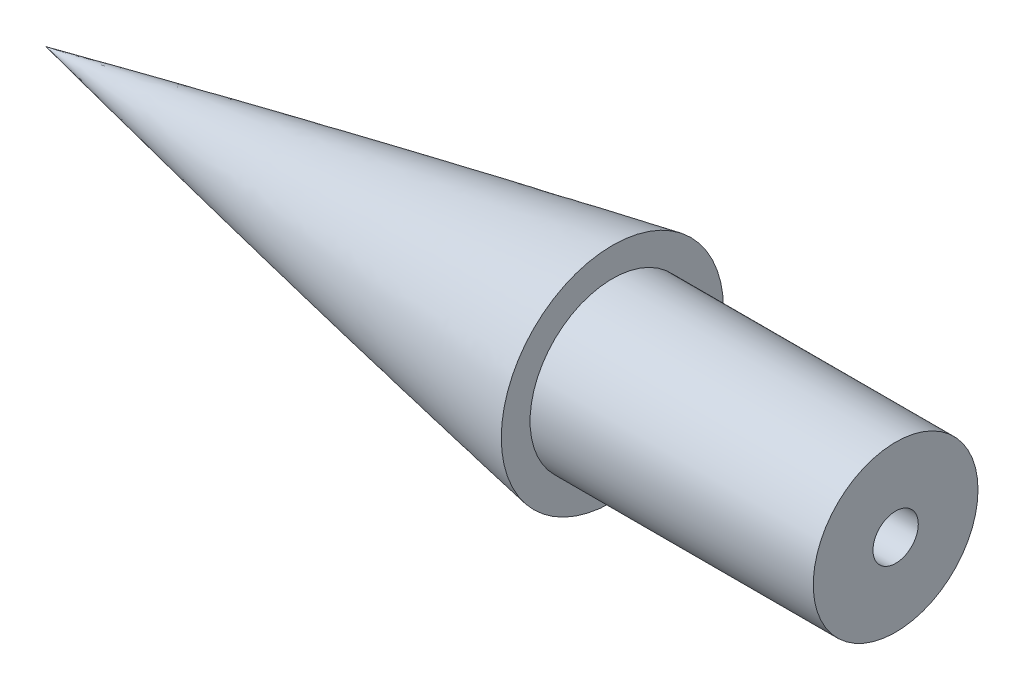
SolidWorks part; units mm, degrees
material "1060 Alloy"
ref_plane "Front Plane" through (0, 0, 0) normal (0, 0, 1) x (1, 0, 0)
ref_plane "Top Plane" through (0, 0, 0) normal (0, 1, 0) x (1, 0, 0)
ref_plane "Right Plane" through (0, 0, 0) normal (1, 0, 0) x (0, 0, -1)
sketch "Sketch1" plane through (0, 0, 0) normal (0, 0, 1) x (1, 0, 0)
  line L0 (0, 0) -> (0, 3483.1) construction
  line L1 (0, 3635.5) -> (0, 3632.5)
  line L2 (0, 3557.2968) -> (-750, 3557.2968) construction
  line L3 (0, 3632.5) -> (0, 3635.5) construction
  line L4 (0, 3632.5) -> (160, 3632.5)
  line L5 (-5, 3627.5) -> (160, 3627.5)
  line L6 (-5, 3630.4966) -> (-5, 3627.5)
  line L7 (-750, 3557.2968) -> (-725.3758, 3557.2968)
  line L8 (160, 3632.5) -> (160, 3627.5)
  line L9 (-650, 3576.9205) -> (-650, 3571.8385)
  line L10 (-650, 3571.8385) -> (-600, 3571.8385)
  line L11 (-600, 3571.8385) -> (-600, 3580.5768)
  line L12 (-2.5, 3630) -> (157.5, 3630) construction
  line L13 (-2.5, 3630) -> (157.5, 3630) construction
  line L14 (-725.628, 3559.7968) -> (-725.628, 3559.7968)
  line L15 (-500, 3598.4287) -> (-500, 3595.9046)
  line L18 (157.5, 3630) -> (157.5, 3630)
  line L21 (-2.5, 3632.9991) -> (-2.5, 3630) construction
  line L22 (-2.5, 3632.9991) -> (-2.5, 3630) construction
  line L23 (-470, 3604.991) -> (-470, 3602.4698)
  line L24 (-320, 3621.3893) -> (-320, 3618.8795)
  line L25 (-350, 3616.1014) -> (-350, 3613.5897)
  line L26 (-40, 3632.7798) -> (-40, 3630.2796)
  line L27 (-10, 3632.9862) -> (-10, 3635.4862)
  line L28 (-170, 3629.0204) -> (-170, 3631.5231)
  line L29 (-200, 3627.4907) -> (-200, 3624.9869)
  line L30 (-40, 3630.2796) -> (-40, 3627.5)
  line L31 (-40, 3627.5) -> (-5, 3627.5)
  line L32 (-10, 3632.9862) -> (-10, 3632.6862)
  line L33 (-170, 3629.0204) -> (-170, 3628.7201)
  line L34 (-320, 3618.8795) -> (-320, 3618.5784)
  line L35 (-470, 3602.4698) -> (-470, 3602.1673)
  line L36 (-600, 3571.8385) -> (-600, 3557.2968)
  line L37 (-600, 3557.2968) -> (-750, 3557.2968)
  arc A0 (0, 3635.5) -> (-750, 3557.2968) centre (0, 0) ccw
  arc A1 (-5, 3630.4966) -> (-600, 3580.5768) centre (0, 0) ccw
  arc A2 (-5, 3630.4966) -> (-748.9685, 3552.4043) centre (0, 0) ccw construction
  arc A5 (-650, 3571.8385) -> (-725.3758, 3557.2968) centre (0, 0) ccw
  arc A6 (-5, 3630.4966) -> (-725.3758, 3557.2968) centre (0, 0) ccw construction
  arc A7 (-2.5, 3632.9991) -> (-725.628, 3559.7968) centre (0, 0) ccw construction
  arc A8 (-2.5, 3632.9991) -> (-725.628, 3559.7968) centre (0, 0) ccw construction
  arc A9 (-500, 3598.4287) -> (-470, 3602.4698) centre (0, 0) cw
  arc A10 (-350, 3616.1014) -> (-320, 3618.8795) centre (0, 0) cw
  arc A11 (-10, 3632.9862) -> (-40, 3632.7798) centre (0, 0) ccw
  arc A12 (-170, 3629.0204) -> (-200, 3627.4907) centre (0, 0) ccw
  arc A13 (-40, 3632.4798) -> (-10, 3632.6862) centre (0, 0) cw
  arc A14 (-200, 3627.1903) -> (-170, 3628.7201) centre (0, 0) cw
  arc A15 (-350, 3615.8) -> (-320, 3618.5784) centre (0, 0) cw
  arc A16 (-500, 3598.1258) -> (-470, 3602.1673) centre (0, 0) cw
  dimension "D1" = 7271
  dimension "D7" = 100
  dimension "D10" = 30
  dimension "D8" = 3633
  dimension "D12" = 3633
  dimension "D15" = 3633
  dimension "D18" = 3633
  dimension "D21" = 3632.7
  dimension "D23" = 3632.7
  dimension "D22" = 3632.7
  dimension "D24" = 3632.7
  dimension "D2" = 152.4
  dimension "D3" = 750
  dimension "D4" = 3
  dimension "D5" = 160
  dimension "D9" = 50
  dimension "D11" = 180
  dimension "D13" = 30
  dimension "D14" = 180
  dimension "D16" = 30
  dimension "D17" = 200
  dimension "D19" = 30
  dimension "D20" = 180
  dimension "D6" = 5
revolve "Revolve1" add sketch "Sketch1" angle 360 about L2
sketch "Sketch3" plane through (-600, 0, 0) normal (1, 0, 0) x (0, 0, -1)
  circle A0 centre (0, 3557.2968) radius 4
  dimension "D1" = 8
extrude "Cut-Extrude1" cut sketch "Sketch3" against normal blind 40
